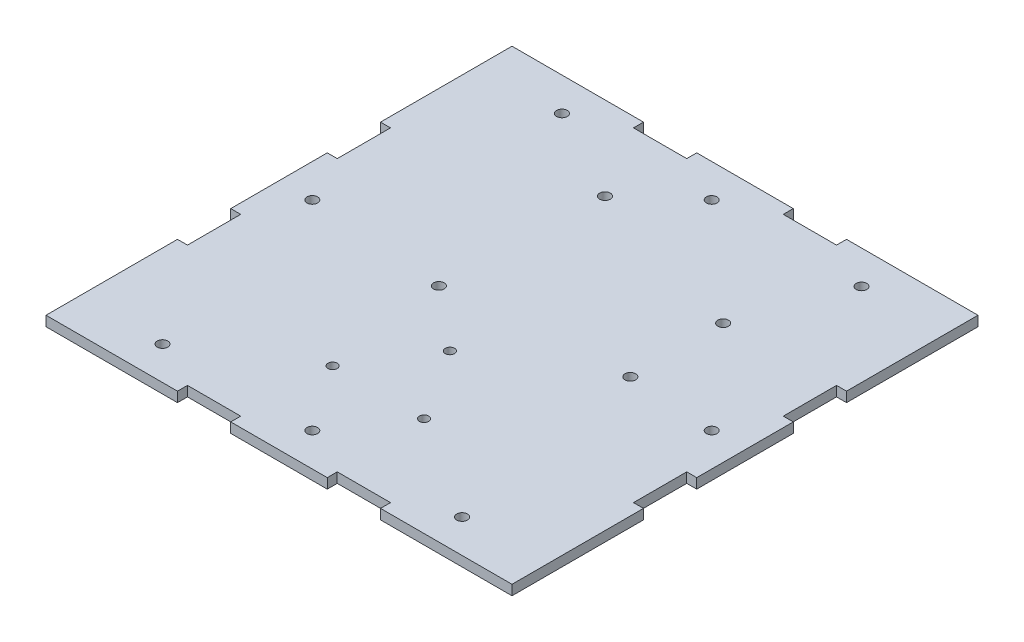
SolidWorks part; units mm, degrees
ref_plane "Front Plane" through (0, 0, 0) normal (0, 0, 1) x (1, 0, 0)
ref_plane "Top Plane" through (0, 0, 0) normal (0, 1, 0) x (1, 0, 0)
ref_plane "Right Plane" through (0, 0, 0) normal (1, 0, 0) x (0, 0, -1)
sketch "Sketch2" plane through (0, 0, 0) normal (0, 1, 0) x (1, 0, 0)
  line L0 (-70, 70) -> (70, -70) construction
  line L1 (-70, 70) -> (70, 70)
  line L2 (-70, 70) -> (-70, -70)
  line L3 (-70, -70) -> (70, -70)
  line L4 (70, 70) -> (70, -70)
  line L5 (70, 70) -> (-70, -70) construction
  line L6 (-0.0302, -29.4237) -> (-0.0302, -47.5058) construction
  line L7 (-50, 50) -> (50, -50) construction
  line L8 (50, 50) -> (-50, 50)
  line L9 (50, 50) -> (50, -50)
  line L10 (50, -50) -> (-50, -50)
  line L11 (-50, 50) -> (-50, -50)
  line L12 (50, 50) -> (-50, -50) construction
  line L13 (-18.6116, -3.3508) -> (-18.6116, 44.9492) construction
  line L14 (33.7884, 1.7492) -> (22.0917, 1.7492)
  line L15 (-18.6116, -3.3508) -> (22.0917, -3.3508)
  line L16 (22.0917, -3.3508) -> (22.0917, 1.7492)
  line L17 (0, 70) -> (0, -70) construction
  line L18 (-70, 0) -> (70, 0) construction
  line L19 (0, 70) -> (0, 50) construction
  line L20 (-50, 0) -> (-70, 0) construction
  line L21 (0, -50) -> (0, -70) construction
  line L22 (50, 0) -> (70, 0) construction
  line L23 (-45, 70) -> (-45, -70) construction
  line L24 (45, 70) -> (45, -70) construction
  line L25 (-45, 50) -> (-45, 70) construction
  line L26 (45, 50) -> (45, 70) construction
  line L27 (-45, -50) -> (-45, -70) construction
  line L28 (45, -50) -> (45, -70) construction
  circle A3 centre (-17.0116, 44.9492) radius 1.6
  circle A4 centre (-18.6116, -3.3508) radius 1.6
  circle A5 centre (33.7884, 29.6492) radius 1.6
  circle A6 centre (33.7884, 1.7492) radius 1.6
  circle A10 centre (0, 60) radius 1.6
  circle A11 centre (-60, 0) radius 1.6
  circle A12 centre (0, -60) radius 1.6
  circle A13 centre (60, 0) radius 1.6
  circle A14 centre (-45, 60) radius 1.6
  circle A15 centre (45, 60) radius 1.6
  circle A16 centre (-45, -60) radius 1.6
  circle A17 centre (45, -60) radius 1.6
  circle A18 centre (-0.0302, -18.6237) radius 1.4
  circle A19 centre (-13.7802, -40.1237) radius 1.4
  circle A20 centre (13.7198, -40.1237) radius 1.4
  point P12 (0, 0)
  point P18 (0, 0)
  point P40 (0, 60)
  point P44 (-60, 0)
  point P49 (0, -60)
  point P54 (60, 0)
  point P63 (-45, 60)
  point P68 (45, 60)
  point P73 (-45, -60)
  point P78 (45, -60)
  dimension "D3" = 25
  dimension "D9" = 3.2
  dimension "D11" = 2.8
  dimension "D1" = 140
  dimension "D2" = 100
  dimension "D4" = 50.8
  dimension "D5" = 27.9
  dimension "D6" = 5.1
  dimension "D7" = 48.3
  dimension "D8" = 40.7033
  dimension "D10" = 25
extrude "Boss-Extrude2" add sketch "Sketch2" along normal blind 3
sketch "Sketch3" plane through (0, 3, 0) normal (0, 1, 0) x (1, 0, 0)
  line L0 (-30.5, 70) -> (-30.5, 67)
  line L1 (-70, 70) -> (70, 70) construction
  line L2 (-30.5, 67) -> (-14.5, 67)
  line L3 (-14.5, 67) -> (-14.5, 70)
  line L4 (-14.5, 70) -> (-30.5, 70)
  line L6 (-1.65, 0) -> (1.65, 0) construction
  line L7 (-70, 70) -> (-70, -70) construction
  line L8 (-14.5, -67) -> (-14.5, -70)
  line L9 (-30.5, -67) -> (-14.5, -67)
  line L10 (-30.5, -70) -> (-30.5, -67)
  line L11 (-14.5, -70) -> (-30.5, -70)
  line L12 (0, -1.65) -> (0, 1.65) construction
  line L13 (30.5, -67) -> (14.5, -67)
  line L14 (30.5, -70) -> (30.5, -67)
  line L15 (14.5, -70) -> (30.5, -70)
  line L16 (14.5, -67) -> (14.5, -70)
  line L17 (14.5, 67) -> (14.5, 70)
  line L18 (30.5, 67) -> (14.5, 67)
  line L19 (30.5, 70) -> (30.5, 67)
  line L20 (14.5, 70) -> (30.5, 70)
  line L21 (-70, 30.5) -> (-67, 30.5)
  line L22 (-67, 30.5) -> (-67, 14.5)
  line L23 (-67, 14.5) -> (-70, 14.5)
  line L25 (-70, 14.5) -> (-70, 30.5)
  line L27 (67, 14.5) -> (70, 14.5)
  line L28 (67, 30.5) -> (67, 14.5)
  line L29 (70, 30.5) -> (67, 30.5)
  line L30 (70, 14.5) -> (70, 30.5)
  line L31 (67, -30.5) -> (67, -14.5)
  line L32 (70, -30.5) -> (67, -30.5)
  line L33 (70, -14.5) -> (70, -30.5)
  line L34 (67, -14.5) -> (70, -14.5)
  line L35 (-67, -14.5) -> (-70, -14.5)
  line L36 (-67, -30.5) -> (-67, -14.5)
  line L37 (-70, -30.5) -> (-67, -30.5)
  line L38 (-70, -14.5) -> (-70, -30.5)
  dimension "D3" = 39.5
  dimension "D1" = 3
  dimension "D2" = 16
  dimension "D4" = 3
  dimension "D5" = 16
  dimension "D6" = 39.5
extrude "Cut-Extrude2" cut sketch "Sketch3" against normal blind 3
